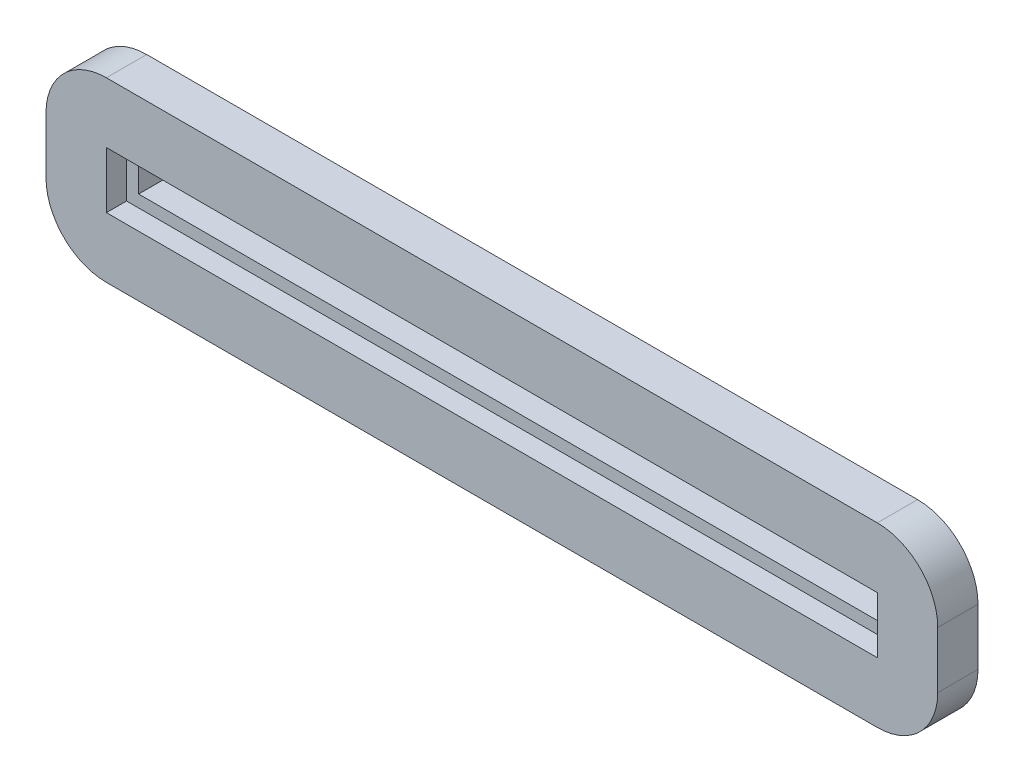
SolidWorks part; units mm, degrees
ref_plane "Plan de face" through (0, 0, 0) normal (0, 0, 1) x (1, 0, 0)
ref_plane "Plan de dessus" through (0, 0, 0) normal (0, 1, 0) x (1, 0, 0)
ref_plane "Plan de droite" through (0, 0, 0) normal (1, 0, 0) x (0, 0, -1)
sketch "Esquisse1" plane through (0, 0, 0) normal (0, 0, 1) x (1, 0, 0)
  line L0 (66.0327, -16) -> (66.0327, -20) construction
  line L1 (66.0327, -20) -> (105.5108, -20) construction
  line L2 (105.5108, -20) -> (105.5108, -16) construction
  line L3 (105.5108, -16) -> (66.0327, -16) construction
  line L4 (66.0327, -16) -> (66.0327, -20)
  line L5 (66.0327, -20) -> (105.5108, -20)
  line L6 (105.5108, -20) -> (105.5108, -16)
  line L7 (105.5108, -16) -> (66.0327, -16)
  line L8 (66.6327, -19.4) -> (104.9108, -19.4)
  line L9 (104.9108, -19.4) -> (104.9108, -16.6)
  line L10 (104.9108, -16.6) -> (66.6327, -16.6)
  line L11 (66.6327, -16.6) -> (66.6327, -19.4)
  dimension "D1" = 0.6
extrude "Boss.-Extru.1" add sketch "Esquisse1" along normal blind 3 contours L8 L9 L10 L11
sketch "Esquisse2" plane through (0, 0, 3) normal (0, 0, 1) x (1, 0, 0)
  line L0 (104.3108, -17.2) -> (67.2327, -17.2)
  line L1 (67.2327, -17.2) -> (67.2327, -18.8)
  line L2 (67.2327, -18.8) -> (104.3108, -18.8)
  line L3 (104.3108, -18.8) -> (104.3108, -17.2)
  line L4 (66.6327, -16.6) -> (66.6327, -19.4)
  line L5 (66.6327, -19.4) -> (104.9108, -19.4)
  line L6 (104.9108, -19.4) -> (104.9108, -16.6)
  line L7 (104.9108, -16.6) -> (66.6327, -16.6)
  line L8 (66.6327, -16.6) -> (66.6327, -19.4)
  line L9 (66.6327, -19.4) -> (104.9108, -19.4)
  line L10 (104.9108, -19.4) -> (104.9108, -16.6)
  line L11 (104.9108, -16.6) -> (66.6327, -16.6)
  dimension "D1" = 0
  dimension "D2" = 0.6
extrude "Enlèv. mat.-Extru.1" cut sketch "Esquisse2" against normal blind 2.5 contours L0 L1 L2 L3
sketch "Esquisse3" plane through (0, 0, 3) normal (0, 0, 1) x (1, 0, 0)
  line L0 (104.9108, -13.6) -> (66.6327, -13.6)
  line L1 (63.6327, -16.6) -> (63.6327, -19.4)
  line L2 (66.6327, -22.4) -> (104.9108, -22.4)
  line L3 (107.9108, -19.4) -> (107.9108, -16.6)
  line L4 (66.6327, -16.6) -> (66.6327, -19.4)
  line L5 (66.6327, -19.4) -> (104.9108, -19.4)
  line L6 (104.9108, -19.4) -> (104.9108, -16.6)
  line L7 (104.9108, -16.6) -> (66.6327, -16.6)
  line L8 (66.6327, -16.6) -> (66.6327, -19.4)
  line L9 (66.6327, -19.4) -> (104.9108, -19.4)
  line L10 (104.9108, -19.4) -> (104.9108, -16.6)
  line L11 (104.9108, -16.6) -> (66.6327, -16.6)
  line L12 (107.9108, -13.6) -> (63.6327, -13.6) construction
  line L13 (107.9108, -22.4) -> (107.9108, -13.6) construction
  line L14 (63.6327, -22.4) -> (107.9108, -22.4) construction
  line L15 (63.6327, -13.6) -> (63.6327, -22.4) construction
  arc A0 (104.9108, -13.6) -> (107.9108, -16.6) centre (104.9108, -16.6) cw
  arc A1 (107.9108, -19.4) -> (104.9108, -22.4) centre (104.9108, -19.4) cw
  arc A2 (66.6327, -22.4) -> (63.6327, -19.4) centre (66.6327, -19.4) cw
  arc A3 (63.6327, -16.6) -> (66.6327, -13.6) centre (66.6327, -16.6) cw
  dimension "D3" = 3
  dimension "D1" = 0
  dimension "D2" = 3
extrude "Boss.-Extru.2" add sketch "Esquisse3" along normal blind 1 and the other way blind 1 separate body
